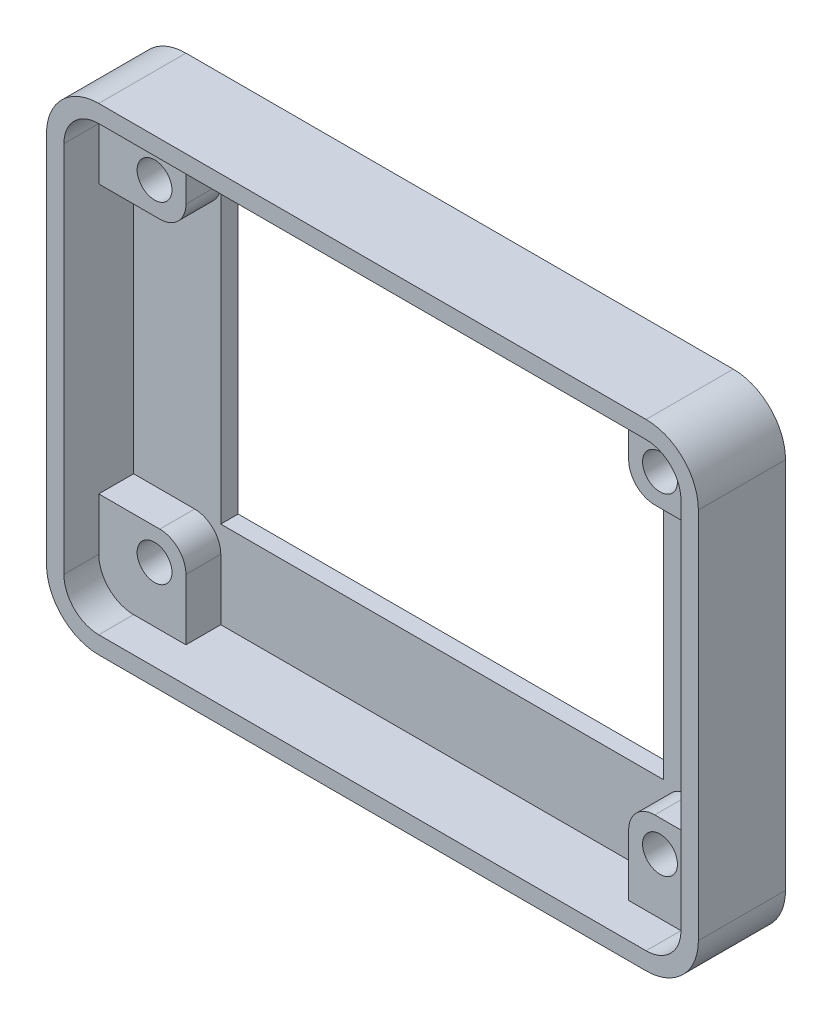
SolidWorks part; units mm, degrees
ref_plane "前视基准面" through (0, 0, 0) normal (0, 0, 1) x (1, 0, 0)
ref_plane "上视基准面" through (0, 0, 0) normal (0, 1, 0) x (1, 0, 0)
ref_plane "右视基准面" through (0, 0, 0) normal (1, 0, 0) x (0, 0, -1)
sketch "草图1" plane through (0, 0, 0) normal (0, 0, 1) x (1, 0, 0)
  line L1 (-18.7, 13.7) -> (18.7, 13.7)
  line L2 (-18.7, 13.7) -> (-18.7, -13.7)
  line L3 (-18.7, -13.7) -> (18.7, -13.7)
  line L4 (18.7, 13.7) -> (18.7, -13.7)
  line L5 (-18.7, 13.7) -> (18.7, -13.7) construction
  line L6 (-18.7, -13.7) -> (18.7, 13.7) construction
  point P0 (0, 0)
  dimension "D1" = 27.4
  dimension "D2" = 37.4
extrude "凸台-拉伸1" add sketch "草图1" along normal blind 5
fillet "圆角1" radius 3 4 edges at (-18.7, -13.7, 2.5) (-18.7, 13.7, 2.5) (18.7, 13.7, 2.5) (18.7, -13.7, 2.5)
shell "抽壳1" thickness 1
sketch "草图2" plane through (0, 0, 0) normal (0, 0, -1) x (-1, 0, 0)
  line L0 (-15.7, 12.7) -> (15.7, 12.7) construction
  line L1 (12.7, 9.7) -> (-12.7, 9.7)
  line L2 (12.7, 9.7) -> (12.7, -7.7)
  line L3 (12.7, -7.7) -> (-12.7, -7.7)
  line L4 (-12.7, 9.7) -> (-12.7, -7.7)
  line L5 (12.7, 9.7) -> (-12.7, -7.7) construction
  line L6 (12.7, -7.7) -> (-12.7, 9.7) construction
  point P0 (0, 0.1)
  point P9 (0, 1)
  dimension "D1" = 25.4
  dimension "D2" = 17.4
  dimension "D3" = 3
  dimension "D4" = 0
  dimension "D5" = 0
extrude "切除-拉伸1" cut sketch "草图2" against normal blind 10
sketch "草图3" plane through (0, 0, 1) normal (0, 0, 1) x (1, 0, 0)
  line L0 (-17.7, 10.7) -> (-17.7, -10.7) construction
  line L1 (-17.7, -7.7) -> (-14.2, -7.7)
  line L2 (-17.7, -7.7) -> (-17.7, -12.7)
  line L3 (-17.7, -12.7) -> (-12.7, -12.7)
  line L4 (-12.7, -9.2) -> (-12.7, -12.7)
  line L5 (-15.7, -12.7) -> (15.7, -12.7) construction
  line L6 (0, 0) -> (0, 4.7636) construction
  line L7 (12.7, -9.2) -> (12.7, -12.7)
  line L8 (17.7, -12.7) -> (12.7, -12.7)
  line L9 (17.7, -7.7) -> (17.7, -12.7)
  line L10 (17.7, -7.7) -> (14.2, -7.7)
  line L11 (0, 0) -> (-5.5296, 0) construction
  line L12 (17.7, 7.7) -> (14.2, 7.7)
  line L13 (17.7, 7.7) -> (17.7, 12.7)
  line L14 (17.7, 12.7) -> (12.7, 12.7)
  line L15 (12.7, 9.2) -> (12.7, 12.7)
  line L16 (-12.7, 9.2) -> (-12.7, 12.7)
  line L17 (-17.7, 12.7) -> (-12.7, 12.7)
  line L18 (-17.7, 7.7) -> (-17.7, 12.7)
  line L19 (-17.7, 7.7) -> (-14.2, 7.7)
  arc A0 (-12.7, -9.2) -> (-14.2, -7.7) centre (-14.2, -9.2) ccw
  arc A1 (12.7, -9.2) -> (14.2, -7.7) centre (14.2, -9.2) cw
  arc A2 (12.7, 9.2) -> (14.2, 7.7) centre (14.2, 9.2) ccw
  arc A3 (-12.7, 9.2) -> (-14.2, 7.7) centre (-14.2, 9.2) cw
  point P11 (-12.7, -7.7)
  point P20 (12.7, -7.7)
  point P34 (12.7, 7.7)
  point P35 (-12.7, 7.7)
  dimension "D3" = 1.5
  dimension "D1" = 5
  dimension "D2" = 5
extrude "凸台-拉伸2" add sketch "草图3" along normal blind 2
sketch "草图4" plane through (0, 0, 0) normal (0, 0, -1) x (-1, 0, 0)
  line L0 (0, 0) -> (-6.8244, 0) construction
  line L1 (0, 0) -> (0, 8.273) construction
  circle A0 centre (14.5, -9.5) radius 1
  circle A1 centre (14.5, 9.5) radius 1
  circle A2 centre (-14.5, 9.5) radius 1
  circle A3 centre (-14.5, -9.5) radius 1
  dimension "D1" = 2
  dimension "D2" = 29
  dimension "D3" = 19
extrude "切除-拉伸2" cut sketch "草图4" against normal through all
